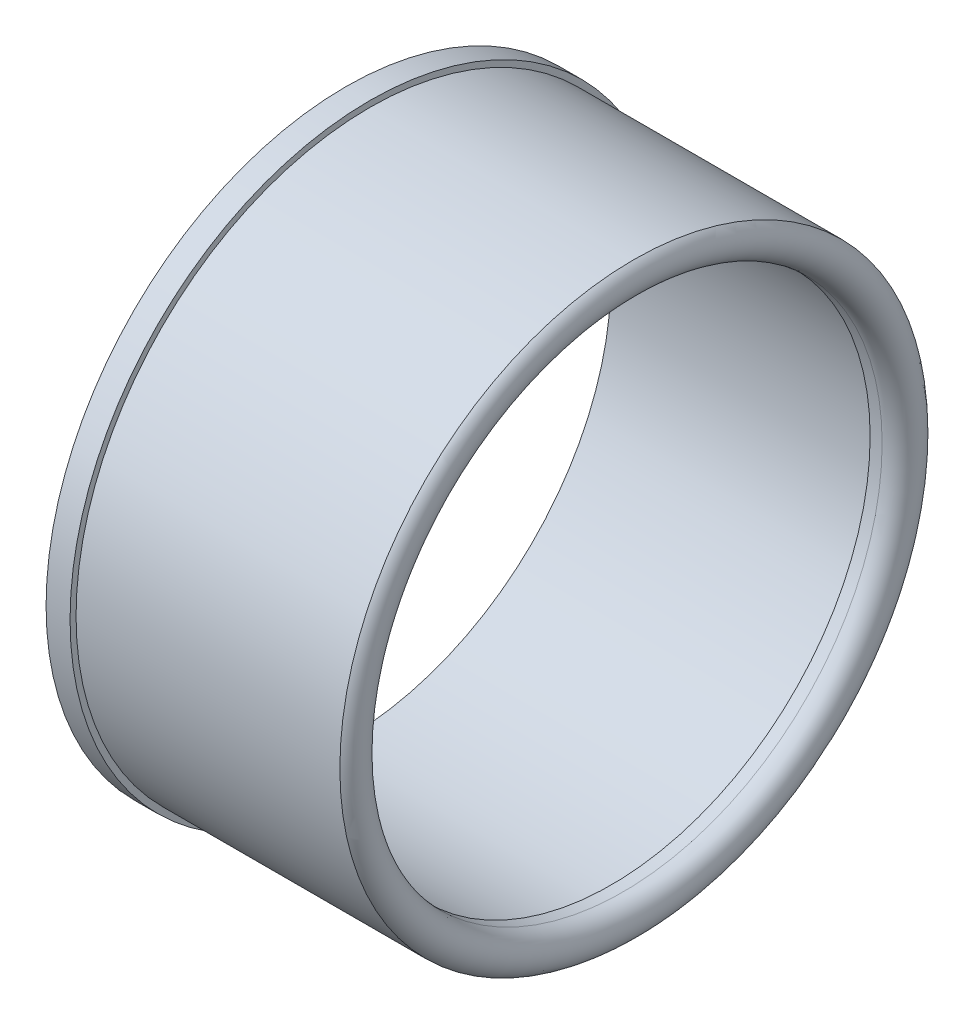
SolidWorks part; units mm, degrees
ref_plane "Front Plane" through (0, 0, 0) normal (0, 0, 1) x (1, 0, 0)
ref_plane "Top Plane" through (0, 0, 0) normal (0, 1, 0) x (1, 0, 0)
ref_plane "Right Plane" through (0, 0, 0) normal (1, 0, 0) x (0, 0, -1)
ref_plane "Plane1" through (0, 0, 0) normal (0, 0, -1) x (-1, 0, 0)
sketch "Sketch1" plane through (0, 0, 0) normal (0, 0, -1) x (-1, 0, 0)
  line L0 (-11.9728, 2.2667) -> (-11.9728, 2.5167)
  line L1 (-11.9728, 2.5167) -> (-0.9121, 2.5167)
  line L2 (-0.9121, 2.5167) -> (-0.9121, 3.9667)
  line L3 (-0.9121, 3.9667) -> (-1.9121, 3.9667)
  line L4 (-1.9121, 3.9667) -> (-1.9121, 3.7167)
  line L5 (-1.9121, 3.7167) -> (-12.9121, 3.7167)
  line L6 (-12.4728, 2.2667) -> (-11.9728, 2.2667)
  line L7 (-12.1757, -8.5333) -> (0.2029, -8.5333) construction
  arc A0 (-12.9121, 3.7167) -> (-12.4728, 2.2667) centre (-12.4728, 3.0583) ccw
  dimension "D1" = 11
  dimension "D2" = 1.45
  dimension "D3" = 0.25
  dimension "D4" = 0.25
  dimension "D5" = 22.1
  dimension "D6" = 1
  dimension "D7" = 0.5
revolve "Revolve1" add sketch "Sketch1" angle 360 about L7
